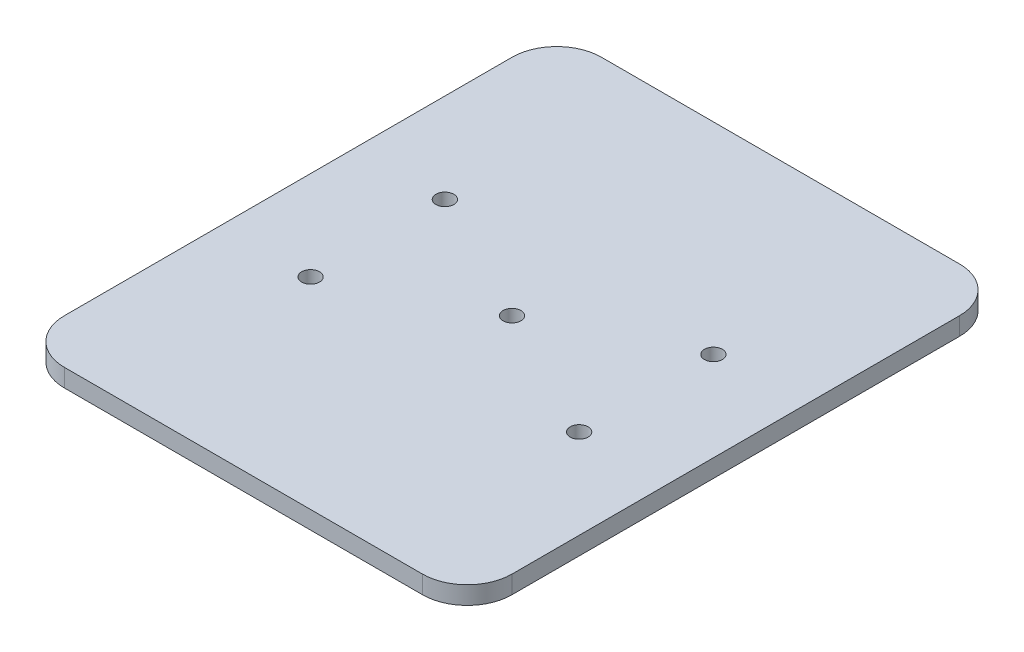
SolidWorks part; units mm, degrees
ref_plane "Front Plane" through (0, 0, 0) normal (0, 0, 1) x (1, 0, 0)
ref_plane "Top Plane" through (0, 0, 0) normal (0, 1, 0) x (1, 0, 0)
ref_plane "Right Plane" through (0, 0, 0) normal (1, 0, 0) x (0, 0, -1)
sketch "Sketch1" plane through (0, 0, 0) normal (0, 1, 0) x (1, 0, 0)
  line L1 (-52.2549, 26.2745) -> (-12.2549, 26.2745)
  line L2 (-57.2549, 21.2745) -> (-57.2549, -28.7255)
  line L3 (-52.2549, -33.7255) -> (-12.2549, -33.7255)
  line L4 (-7.2549, 21.2745) -> (-7.2549, -28.7255)
  arc A0 (-57.2549, -28.7255) -> (-52.2549, -33.7255) centre (-52.2549, -28.7255) ccw
  arc A1 (-12.2549, -33.7255) -> (-7.2549, -28.7255) centre (-12.2549, -28.7255) ccw
  arc A2 (-12.2549, 26.2745) -> (-7.2549, 21.2745) centre (-12.2549, 21.2745) cw
  arc A3 (-52.2549, 26.2745) -> (-57.2549, 21.2745) centre (-52.2549, 21.2745) ccw
  circle A4 centre (-32.2549, -3.7255) radius 1
  circle A5 centre (-47.2549, 3.7745) radius 1
  circle A6 centre (-47.2549, -11.2255) radius 1
  circle A7 centre (-17.2549, 3.7745) radius 1
  circle A8 centre (-17.2549, -11.2255) radius 1
  point P6 (-57.2549, -33.7255)
  point P11 (-7.2549, 26.2745)
  point P14 (-57.2549, 26.2745)
  dimension "D3" = 5
  dimension "D4" = 30
  dimension "D6" = 22.5
  dimension "D8" = 15
  dimension "D10" = 10
  dimension "D1" = 60
  dimension "D2" = 50
  dimension "D5" = 25
  dimension "D7" = 10
  dimension "D9" = 10
  dimension "D11" = 10
  dimension "D12" = 15
  dimension "D13" = 22.5
extrude "Boss-Extrude1" add sketch "Sketch1" along normal blind 2
